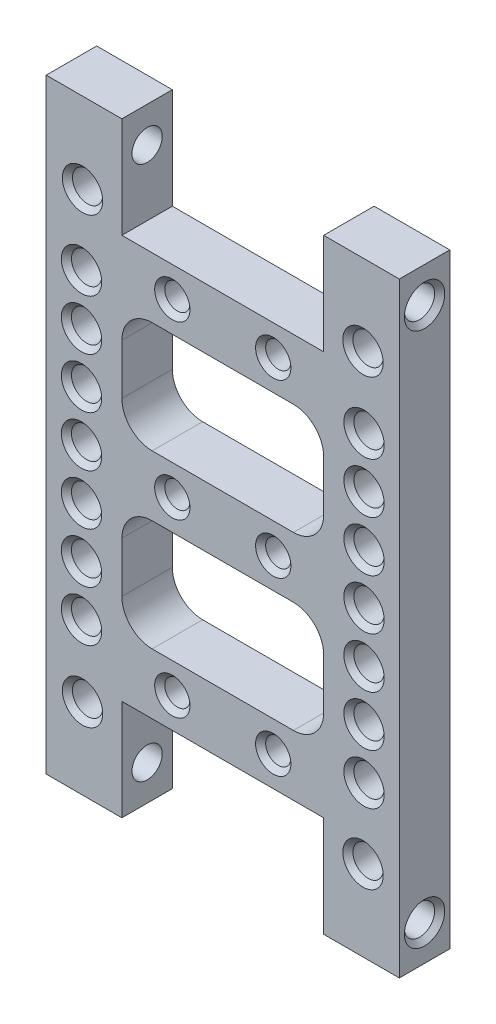
SolidWorks part; units mm, degrees
material "6063-O"
ref_plane "前视基准面" through (0, 0, 0) normal (0, 0, 1) x (1, 0, 0)
ref_plane "上视基准面" through (0, 0, 0) normal (0, 1, 0) x (1, 0, 0)
ref_plane "右视基准面" through (0, 0, 0) normal (1, 0, 0) x (0, 0, -1)
sketch "草图1" plane through (0, 0, 0) normal (0, 0, 1) x (1, 0, 0)
  line L1 (-17.5, -30) -> (17.5, -30)
  line L2 (-17.5, -30) -> (-17.5, 30)
  line L3 (-17.5, 30) -> (17.5, 30)
  line L4 (17.5, -30) -> (17.5, 30)
  line L5 (-17.5, -30) -> (17.5, 30) construction
  line L6 (-17.5, 30) -> (17.5, -30) construction
  point P0 (0, 0)
  dimension "D1" = 60
  dimension "D2" = 35
extrude "凸台-拉伸1" add sketch "草图1" along normal blind 5
sketch "草图2" plane through (0, 0, 5) normal (0, 0, 1) x (1, 0, 0)
  line L0 (0, 30) -> (0, -30) construction
  line L1 (17.5, 30) -> (-17.5, 30) construction
  line L2 (-17.5, -30) -> (17.5, -30) construction
  line L3 (-23.1473, 0) -> (22.9425, 0) construction
  line L4 (10, 20) -> (-10, 20)
  line L5 (10, 20) -> (10, 30)
  line L6 (10, 30) -> (-10, 30)
  line L7 (-10, 20) -> (-10, 30)
  line L8 (10, 20) -> (-10, 30) construction
  line L9 (10, 30) -> (-10, 20) construction
  line L10 (10, -30) -> (-10, -20) construction
  line L11 (10, -20) -> (-10, -30) construction
  line L12 (-10, -20) -> (-10, -30)
  line L13 (10, -30) -> (-10, -30)
  line L14 (10, -20) -> (10, -30)
  line L15 (10, -20) -> (-10, -20)
  line L16 (-14, 30) -> (-14, -30) construction
  line L17 (14, 30) -> (14, -30) construction
  line L18 (-10, 3) -> (10, 14) construction
  line L19 (-10, 14) -> (10, 3) construction
  line L20 (10, 11) -> (10, 6)
  line L21 (-7, 3) -> (7, 3)
  line L22 (-10, 11) -> (-10, 6)
  line L23 (-7, 14) -> (7, 14)
  line L24 (-5, 17) -> (5, 17) construction
  line L25 (-7, -14) -> (7, -14)
  line L26 (-10, -11) -> (-10, -6)
  line L27 (-7, -3) -> (7, -3)
  line L28 (10, -11) -> (10, -6)
  line L29 (-10, -14) -> (10, -3) construction
  line L30 (-10, -3) -> (10, -14) construction
  circle A0 centre (-14, 0) radius 1.5
  circle A1 centre (-14, -15) radius 1.5
  circle A2 centre (14, -15) radius 1.5
  circle A3 centre (14, 0) radius 1.5
  circle A4 centre (-14, -10) radius 1.5
  circle A5 centre (-13.9, -22) radius 1.5
  circle A6 centre (13.9, -22) radius 1.5
  circle A7 centre (14, -10) radius 1.5
  circle A8 centre (-13.9, 22) radius 1.5
  circle A9 centre (13.9, 22) radius 1.5
  circle A10 centre (14, 10) radius 1.5
  circle A11 centre (-14, 10) radius 1.5
  circle A12 centre (14, 15) radius 1.5
  circle A13 centre (-14, 15) radius 1.5
  arc A14 (10, -6) -> (7, -3) centre (7, -6) ccw
  arc A15 (10, -11) -> (7, -14) centre (7, -11) cw
  arc A16 (-7, -14) -> (-10, -11) centre (-7, -11) cw
  arc A17 (-10, -6) -> (-7, -3) centre (-7, -6) cw
  arc A18 (-10, 6) -> (-7, 3) centre (-7, 6) ccw
  arc A19 (-7, 14) -> (-10, 11) centre (-7, 11) ccw
  arc A20 (10, 11) -> (7, 14) centre (7, 11) ccw
  arc A21 (10, 6) -> (7, 3) centre (7, 6) cw
  circle A22 centre (-5, 0) radius 0.5
  circle A23 centre (5, 0) radius 0.5
  circle A24 centre (-14, -5) radius 1.5
  circle A25 centre (14, -5) radius 1.5
  circle A26 centre (14, 5) radius 1.5
  circle A27 centre (-14, 5) radius 1.5
  circle A28 centre (-5, 17) radius 0.5
  circle A29 centre (5, 17) radius 0.5
  circle A30 centre (5, -17) radius 0.5
  circle A31 centre (-5, -17) radius 0.5
  point P6 (0, 25)
  point P18 (0, -25)
  point P56 (0, -8.5)
  point P84 (0, 8.5)
  dimension "D5" = 3
  dimension "D6" = 15
  dimension "D7" = 8
  dimension "D8" = 10
  dimension "D12" = 3
  dimension "D13" = 10
  dimension "D14" = 5
  dimension "D15" = 10
  dimension "D17" = 5
  dimension "D18" = 5
  dimension "D19" = 1
  dimension "D1" = 10
  dimension "D2" = 20
  dimension "D3" = 14
  dimension "D4" = 14
  dimension "D9" = 3
  dimension "D10" = 6
  dimension "D11" = 20
  dimension "D16" = 3
  dimension "D20" = 13.9
extrude "切除-拉伸1" cut sketch "草图2" against normal through all
sketch "草图3" plane through (17.5, 0, 0) normal (1, 0, 0) x (0, 0, -1)
  line L0 (-2.5, 30) -> (-2.5, -30) construction
  line L1 (-5, 30) -> (0, 30) construction
  line L2 (-5, -30) -> (0, -30) construction
  circle A0 centre (-2.5, -26.5) radius 1.5
  circle A1 centre (-2.5, 26.5) radius 1.5
  dimension "D1" = 3
  dimension "D2" = 3.5
  dimension "D3" = 3.5
extrude "切除-拉伸2" cut sketch "草图3" against normal through all
hole_wizard "M3 螺纹孔1" positions "草图5" profile "草图4" tap size "M3" standard "GB" end condition through all
sketch "草图5" plane through (0, 0, 5) normal (0, 0, 1) x (1, 0, 0)
  point P1 (-5, 17)
  point P4 (5, 17)
  point P7 (-5, 0)
  point P10 (5, 0)
  point P13 (-5, -17)
  point P16 (5, -17)
sketch "草图4" plane through (-5, 17, 5) normal (1, 0, 0) x (0, -1, 0)
  line L0 (0, 0) -> (0, 5)
  line L1 (0, 5) -> (1.25, 5)
  line L2 (1.25, 5) -> (1.25, 0)
  line L5 (1.25, 0) -> (0, 0)
  line L11 (0, -6.35) -> (0, 107.95) construction
  dimension "通孔螺纹孔钻头直径" = 2.5
  dimension "通孔螺纹孔钻头深度" = 5
cosmetic thread "孔螺蚊线1" parameters "D2"=3
cosmetic thread "孔螺蚊线2" parameters "D2"=3
cosmetic thread "孔螺蚊线3" parameters "D2"=3
cosmetic thread "孔螺蚊线4" parameters "D2"=3
cosmetic thread "孔螺蚊线5" parameters "D2"=3
cosmetic thread "孔螺蚊线6" parameters "D2"=3
chamfer "倒角1" distance 0.5 angle 45 51 edges at (15.5, 15, 5) (6.25, 0, 0) (-3.75, 0, 0) (-3.75, -17, 0) (6.25, -17, 0) (17.5, -26.5, 1) (17.5, 26.5, 1) (-17.5, 26.5, 1) (-17.5, -26.5, 1) (-12.4, -22, 0) (-12.5, -15, 0) (-12.5, -10, 0) (-12.5, -5, 0) (-12.5, 0, 0) (-15.5, 5, 0) (-15.5, 10, 0) (-15.5, 15, 0) (-15.4, 22, 0) (-3.75, 17, 0) (6.25, 17, 0) (15.4, 22, 0) (15.5, 10, 0) (15.5, 5, 0) (12.5, 0, 0) (12.5, -5, 0) (12.5, -10, 0) (12.5, -15, 0) (12.4, -22, 0) (6.25, -17, 5) (-3.75, -17, 5) (6.25, 0, 5) (-3.75, 0, 5) (-3.75, 17, 5) (6.25, 17, 5) (15.4, 22, 5) (15.5, 10, 5) (15.5, 5, 5) (12.5, 0, 5) (12.5, -5, 5) (12.5, -10, 5) (12.5, -15, 5) (12.4, -22, 5) (-12.4, -22, 5) (-12.5, -15, 5) (-12.5, -10, 5) (-12.5, -5, 5) (-12.5, 0, 5) (-15.5, 5, 5) (-15.5, 10, 5) (-15.5, 15, 5) (-15.4, 22, 5)
